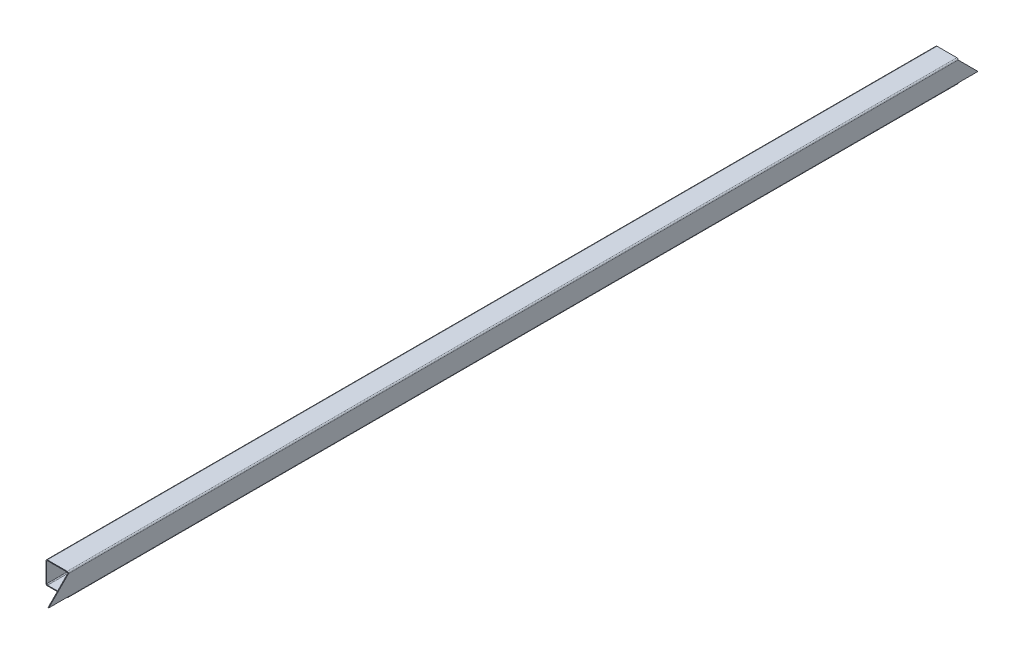
SolidWorks part; units mm, degrees
material "AISI 1020"
ref_plane "Спереди" through (0, 0, 0) normal (0, 0, 1) x (1, 0, 0)
ref_plane "Сверху" through (0, 0, 0) normal (0, 1, 0) x (1, 0, 0)
ref_plane "Справа" through (0, 0, 0) normal (1, 0, 0) x (0, 0, -1)
sketch "Эскиз1" plane through (0, 0, 0) normal (0, 0, 1) x (1, 0, 0)
  line B0 (-44, 50) -> (44, 50)
  line B1 (-50, 44) -> (-50, -44)
  line B2 (-44, -50) -> (44, -50)
  line B3 (50, 44) -> (50, -44)
  line B4 (-50, 50) -> (50, -50) construction
  line B5 (-50, -50) -> (50, 50) construction
  line B6 (-43, 47) -> (43, 47)
  line B7 (-47, 43) -> (-47, -43)
  line B8 (-43, -47) -> (43, -47)
  line B9 (47, 43) -> (47, -43)
  line B10 (-47, 47) -> (47, -47) construction
  line B11 (-47, -47) -> (47, 47) construction
  arc B12 (-50, -44) -> (-44, -50) centre (-44, -44) ccw
  arc B13 (44, -50) -> (50, -44) centre (44, -44) ccw
  arc B14 (44, 50) -> (50, 44) centre (44, 44) cw
  arc B15 (-44, 50) -> (-50, 44) centre (-44, 44) ccw
  arc B16 (-47, -43) -> (-43, -47) centre (-43, -43) ccw
  arc B17 (43, -47) -> (47, -43) centre (43, -43) ccw
  arc B18 (43, 47) -> (47, 43) centre (43, 43) cw
  arc B19 (-43, 47) -> (-47, 43) centre (-43, 43) ccw
sketch_block_instance "Блок1-1"
sketch_block "Блок1" parameters "D3"=6, "D4"=4, "D1"=100, "D2"=3
extrude "Бобышка-Вытянуть1" add sketch "Эскиз1" against normal blind 3950
sketch "Эскиз2" plane through (50, 0, 0) normal (1, 0, 0) x (0, 0, -1)
  line L0 (0, -44) -> (0, 44) construction
  line L1 (0, -44) -> (0, 44)
  line L2 (0, -44) -> (-88, -44)
  line L3 (-88, -44) -> (0, 44)
  line L4 (3950, -44) -> (3950, 44) construction
  line L5 (3950, -44) -> (3950, 44)
  line L6 (3950, -44) -> (4038, -44)
  line L7 (4038, -44) -> (3950, 44)
extrude "Бобышка-Вытянуть2" add sketch "Эскиз2" against normal up to surface (3 mm away) up to face at (47, 0, -1975)
